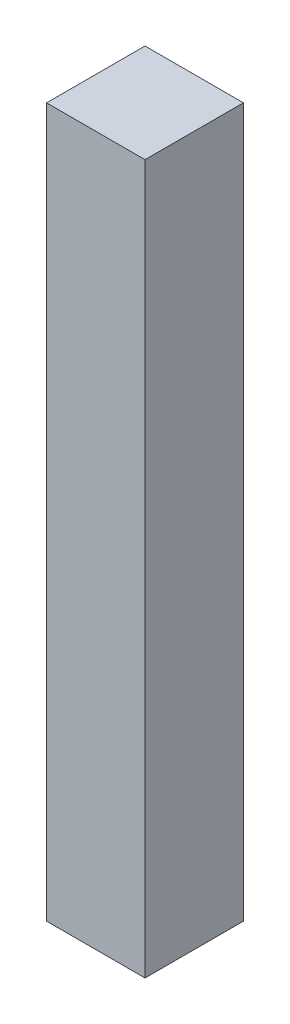
SolidWorks part; units mm, degrees
ref_plane "Front Plane" through (0, 0, 0) normal (0, 0, 1) x (1, 0, 0)
ref_plane "Top Plane" through (0, 0, 0) normal (0, 1, 0) x (1, 0, 0)
ref_plane "Right Plane" through (0, 0, 0) normal (1, 0, 0) x (0, 0, -1)
sketch "Sketch1" plane through (0, 0, 0) normal (0, 1, 0) x (1, 0, 0)
  line L1 (-50, -50) -> (50, -50)
  line L2 (-50, -50) -> (-50, 50)
  line L3 (-50, 50) -> (50, 50)
  line L4 (50, -50) -> (50, 50)
  line L5 (-50, -50) -> (50, 50) construction
  line L6 (-50, 50) -> (50, -50) construction
  point P0 (0, 0)
  dimension "D1" = 100
  dimension "D2" = 100
extrude "Boss-Extrude1" add sketch "Sketch1" along normal blind 720
